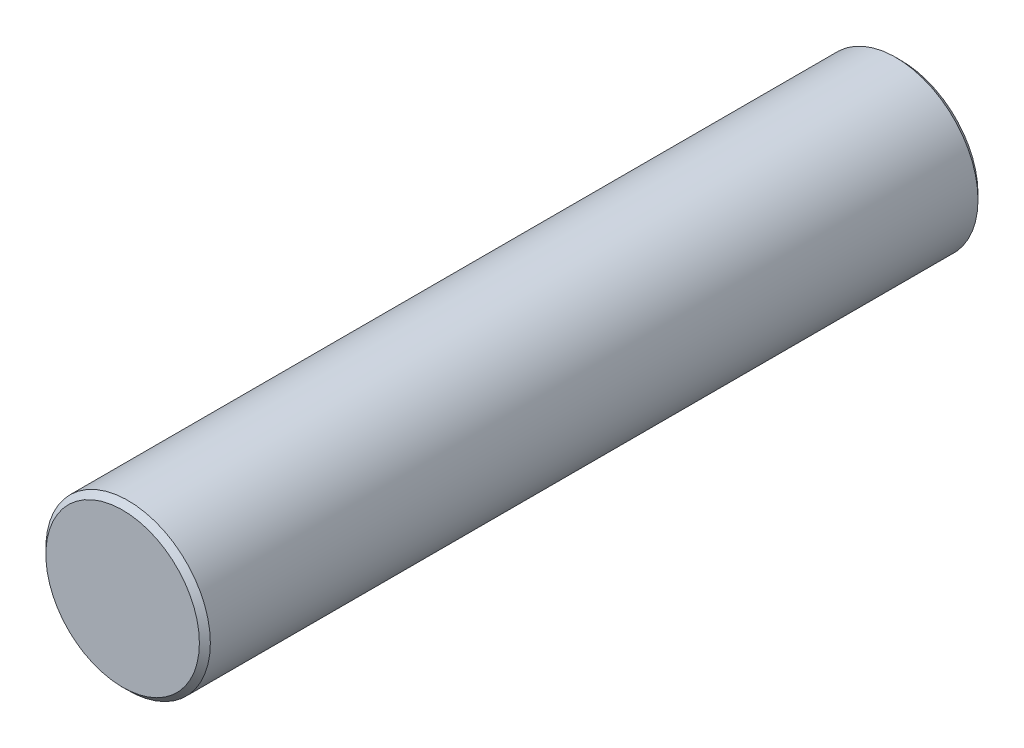
SolidWorks part; units mm, degrees
ref_plane "Front Plane" through (0, 0, 0) normal (1, 0, 0) x (0, 1, 0)
ref_plane "Top Plane" through (0, 0, 0) normal (0, 0, 1) x (0, 1, 0)
ref_plane "Right Plane" through (0, 0, 0) normal (0, 1, 0) x (-1, 0, 0)
sketch "Sketch1" plane through (0, 0, 0) normal (0, 0, 1) x (0, 1, 0)
  circle A0 centre (0, 0) radius 3
  dimension "D1" = 6
extrude "Boss-Extrude1" add sketch "Sketch1" along normal mid plane 28.4
chamfer "Chamfer1" distance 0.2 angle 45 2 edges at (3, 0, -14.2) (3, 0, 14.2)
